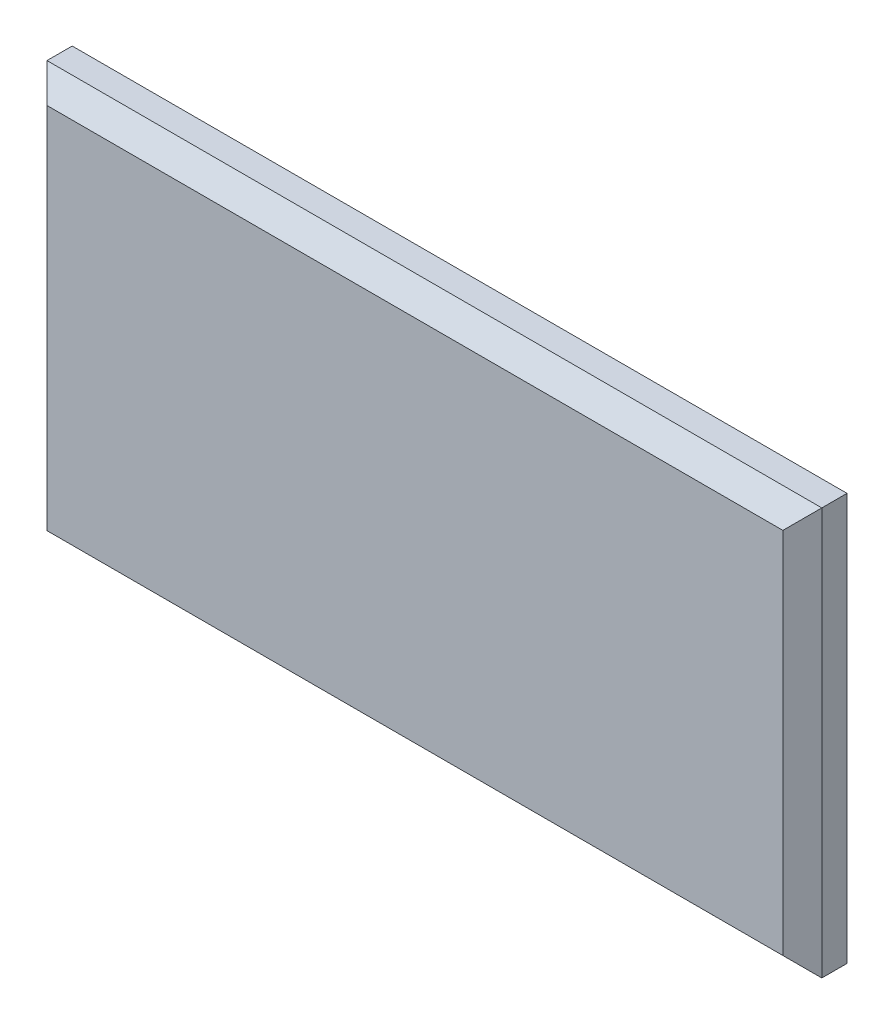
SolidWorks part; units mm, degrees
ref_plane "Front Plane" through (0, 0, 0) normal (0, 0, 1) x (1, 0, 0)
ref_plane "Top Plane" through (0, 0, 0) normal (0, 1, 0) x (1, 0, 0)
ref_plane "Right Plane" through (0, 0, 0) normal (1, 0, 0) x (0, 0, -1)
sketch3d "3DSketch1"
  line L0 (-0.0576, -0.0297, 0.0584) -> (-0.0548, -0.0269, 0.0613)
  line L1 (-0.0548, -0.0269, 0.0613) -> (0.0526, -0.0269, 0.0613)
  line L2 (0.0526, -0.0269, 0.0613) -> (0.0554, -0.0297, 0.0584)
  line L3 (0.0554, -0.0297, 0.0584) -> (-0.0576, -0.0297, 0.0584)
  line L4 (-0.0576, -0.0297, 0.0444) -> (-0.0548, -0.0269, 0.0416)
  line L5 (-0.0548, -0.0269, 0.0416) -> (0.0526, -0.0269, 0.0416)
  line L6 (0.0526, -0.0269, 0.0416) -> (0.0554, -0.0297, 0.0444)
  line L7 (0.0554, -0.0297, 0.0444) -> (-0.0576, -0.0297, 0.0444)
  line L8 (0.0554, -0.0297, 0.0444) -> (0.0554, -0.0297, 0.0584)
  line L9 (-0.0576, -0.0297, 0.0584) -> (-0.0576, -0.0297, 0.0444)
  line L10 (-0.0548, -0.0269, 0.0613) -> (-0.0548, 0.0269, 0.0613)
  line L11 (-0.0548, 0.0269, 0.0613) -> (-0.0576, 0.0297, 0.0584)
  line L12 (-0.0576, 0.0297, 0.0584) -> (-0.0576, -0.0297, 0.0584)
  line L13 (-0.0576, 0.0297, 0.0584) -> (-0.0576, 0.0297, 0.0444)
  line L14 (-0.0576, 0.0297, 0.0444) -> (-0.0576, -0.0297, 0.0444)
  line L15 (-0.0548, -0.0269, 0.0416) -> (-0.0548, 0.0269, 0.0416)
  line L16 (-0.0548, 0.0269, 0.0416) -> (-0.0576, 0.0297, 0.0444)
  line L17 (-0.0548, 0.0269, 0.0613) -> (0.0526, 0.0269, 0.0613)
  line L18 (0.0526, 0.0269, 0.0613) -> (0.0526, -0.0269, 0.0613)
  line L19 (0.0554, -0.0297, 0.0584) -> (0.0554, 0.0297, 0.0584)
  line L20 (0.0554, 0.0297, 0.0584) -> (0.0526, 0.0269, 0.0613)
  point P28 (0, 0, 0)
ref_plane "Plane1" through (0, 0, 0.0416) normal (0, 0, 1) x (1, 0, 0)
ref_plane "Plane2" through (0, -0.0297, 0) normal (0, 1, 0) x (1, 0, 0)
sketch "Sketch6" plane through (0, -0.0297, 0) normal (0, 1, 0) x (1, 0, 0)
  line L0 (-0.0576, -0.0444) -> (-0.0548, -0.0416)
  line L2 (-0.0576, -0.0444) -> (-0.0576, -0.0584)
  line L4 (0.0554, -0.0444) -> (0.0554, -0.0584)
  line L5 (-0.0548, -0.0416) -> (0.0526, -0.0416)
  line L6 (0.0526, -0.0416) -> (0.0554, -0.0444)
  line L7 (-0.0576, -0.0584) -> (-0.0548, -0.0613)
  line L8 (-0.0548, -0.0613) -> (0.0526, -0.0613)
  line L9 (0.0526, -0.0613) -> (0.0554, -0.0584)
extrude "Boss-Extrude2" add sketch "Sketch6" along normal up to vertex (0.0594 mm away)
ref_plane "Plane3" through (-0.0576, 0, 0) normal (1, 0, 0) x (0, 0, -1)
sketch "Sketch10" plane through (-0.0576, 0, 0) normal (1, 0, 0) x (0, 0, -1)
  line L0 (-0.0613, 0.0269) -> (-0.0584, 0.0297)
  line L1 (-0.0416, 0.0269) -> (-0.0444, 0.0297)
  line L5 (-0.0584, -0.0297) -> (-0.0613, -0.0269)
  line L6 (-0.0444, -0.0297) -> (-0.0416, -0.0269)
  line L8 (-0.0613, -0.0269) -> (-0.0613, -0.0297)
  line L9 (-0.0613, 0.0297) -> (-0.0584, 0.0297)
  line L10 (-0.0613, 0.0297) -> (-0.0613, 0.0269)
  line L11 (-0.0613, -0.0297) -> (-0.0584, -0.0297)
  line L12 (-0.0416, 0.0297) -> (-0.0416, 0.0269)
  line L13 (-0.0416, -0.0269) -> (-0.0416, -0.0297)
  line L14 (-0.0444, 0.0297) -> (-0.0416, 0.0297)
  line L15 (-0.0444, -0.0297) -> (-0.0416, -0.0297)
extrude "Cut-Extrude2" cut sketch "Sketch10" along normal through all
sketch "Sketch11" plane through (-0.0576, 0, 0) normal (-1, 0, 0) x (0, 0, 1)
  line L0 (0.0548, 0.0297) -> (0.0548, -0.0297)
  line L1 (0.0444, 0.0297) -> (0.0584, 0.0297) construction
  line L2 (0.0444, -0.0297) -> (0.0584, -0.0297) construction
  line L8 (0.0416, 0.0269) -> (0.0416, -0.0269) construction
  line L9 (0.0548, 0.0297) -> (0.0444, 0.0297)
  line L10 (0.0444, 0.0297) -> (0.0416, 0.0269)
  line L11 (0.0416, 0.0269) -> (0.0416, -0.0269)
  line L12 (0.0416, -0.0269) -> (0.0444, -0.0297)
  line L13 (0.0444, -0.0297) -> (0.0548, -0.0297)
  dimension "D1" = 0.0132
extrude "Cut-Extrude6" cut sketch "Sketch11" against normal through all
sketch "Sketch14" plane through (-0.0576, 0, 0) normal (-1, 0, 0) x (0, 0, 1)
  line L0 (0.0548, -0.0297) -> (0.0548, 0.0297) construction
  line L1 (0.0548, 0.0063) -> (0.0561, 0.0063)
  line L2 (0.0548, 0.0063) -> (0.0548, -0.0062)
  line L3 (0.0548, -0.0062) -> (0.0561, -0.0062)
  line L4 (0.0561, 0.0063) -> (0.0561, -0.0062)
  line L5 (0.0548, 0.0063) -> (0.0518, 0.0063) construction
  dimension "D1" = 0.0013
extrude "Cut-Extrude7" cut sketch "Sketch14" against normal blind 0.005
sketch "Sketch15" plane through (0, 0, 0.0548) normal (0, 0, -1) x (-1, 0, 0)
  line L0 (-0.0554, 0.0297) -> (0.0576, 0.0297) construction
  line L1 (-0.0529, 0.0272) -> (0.0551, 0.0272)
  line L2 (-0.0529, 0.0272) -> (-0.0529, -0.0272)
  line L3 (-0.0529, -0.0272) -> (0.0551, -0.0272)
  line L4 (0.0551, 0.0272) -> (0.0551, -0.0272)
  line L5 (-0.0554, -0.0297) -> (-0.0554, 0.0297) construction
  line L6 (-0.0554, -0.0297) -> (0.0576, -0.0297) construction
  line L8 (0.0576, -0.0297) -> (0.0576, -0.0062) construction
  dimension "D1" = 0.0025
  dimension "D2" = 0.0025
  dimension "D3" = 0.0025
  dimension "D4" = 0.0025
extrude "Cut-Extrude8" cut sketch "Sketch15" against normal blind 0.005
